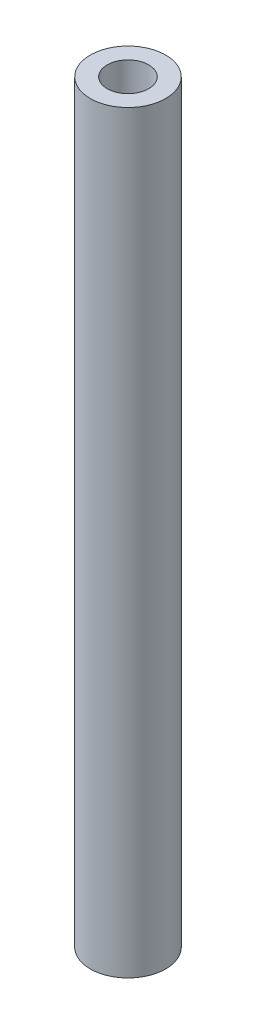
SolidWorks part; units mm, degrees
ref_plane "Front Plane" through (0, 0, 0) normal (0, 0, 1) x (1, 0, 0)
ref_plane "Top Plane" through (0, 0, 0) normal (0, 1, 0) x (1, 0, 0)
ref_plane "Right Plane" through (0, 0, 0) normal (1, 0, 0) x (0, 0, -1)
sketch "Sketch1" plane through (0, 0, 0) normal (0, 1, 0) x (1, 0, 0)
  circle A0 centre (0, 0) radius 2
  circle A1 centre (0, 0) radius 1.1
  dimension "D1" = 4
  dimension "D2" = 2.2
extrude "Boss-Extrude1" add sketch "Sketch1" along normal blind 40
